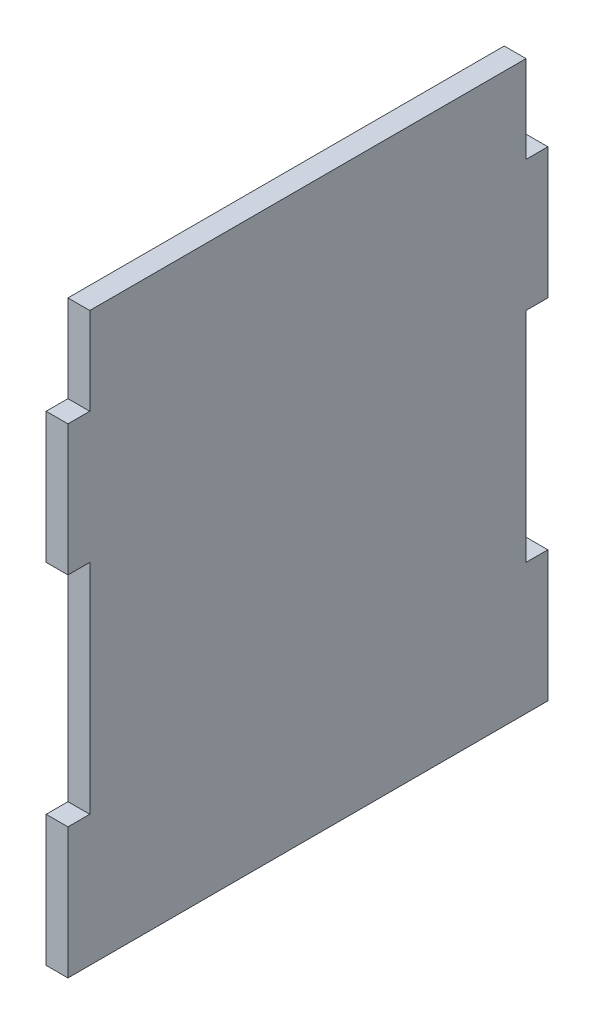
SolidWorks part; units mm, degrees
ref_plane "Front Plane" through (0, 0, 0) normal (0, 0, 1) x (1, 0, 0)
ref_plane "Top Plane" through (0, 0, 0) normal (0, 1, 0) x (1, 0, 0)
ref_plane "Right Plane" through (0, 0, 0) normal (1, 0, 0) x (0, 0, -1)
sketch "Sketch1" plane through (0, 0, 0) normal (1, 0, 0) x (0, 0, -1)
  line L0 (0, 0) -> (-3.175, 0)
  line L1 (0, 0) -> (63.5, 0)
  line L2 (0, 19.05) -> (0, 50.8)
  line L3 (0, 82.55) -> (63.5, 82.55)
  line L4 (63.5, 19.05) -> (63.5, 50.8)
  line L5 (-3.175, 0) -> (-3.175, 19.05)
  line L6 (-3.175, 19.05) -> (0, 19.05)
  line L7 (-3.175, 69.85) -> (0, 69.85)
  line L8 (-3.175, 50.8) -> (-3.175, 69.85)
  line L9 (0, 50.8) -> (-3.175, 50.8)
  line L10 (0, 69.85) -> (0, 82.55)
  line L11 (31.75, 82.55) -> (31.75, 0) construction
  line L12 (63.5, 0) -> (66.675, 0)
  line L13 (66.675, 0) -> (66.675, 19.05)
  line L14 (66.675, 19.05) -> (63.5, 19.05)
  line L15 (63.5, 50.8) -> (66.675, 50.8)
  line L16 (66.675, 50.8) -> (66.675, 69.85)
  line L17 (66.675, 69.85) -> (63.5, 69.85)
  line L18 (63.5, 69.85) -> (63.5, 82.55)
  dimension "D1" = 82.55
  dimension "D2" = 63.5
  dimension "D4" = 3.175
  dimension "D5" = 19.05
  dimension "D6" = 2
extrude "Boss-Extrude1" add sketch "Sketch1" along normal blind 3.175
